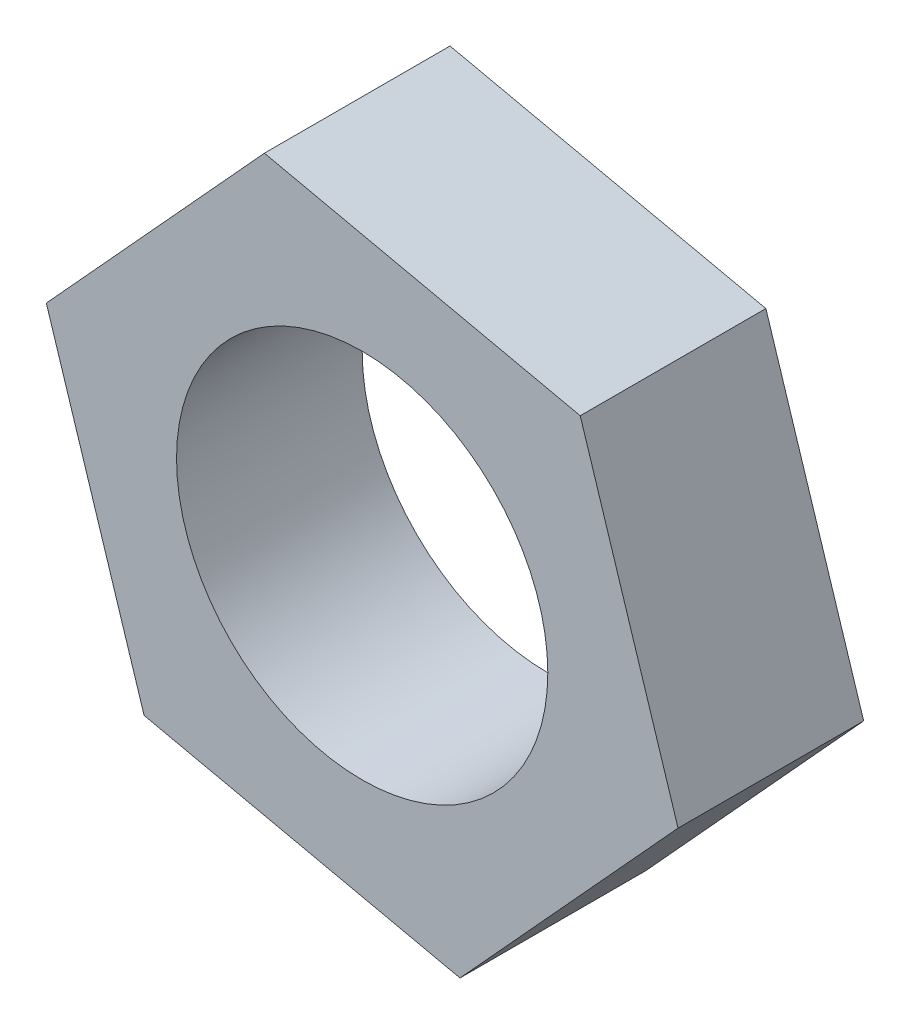
SolidWorks part; units mm, degrees
ref_plane "Front Plane" through (0, 0, 0) normal (0, 0, 1) x (1, 0, 0)
ref_plane "Top Plane" through (0, 0, 0) normal (0, 1, 0) x (1, 0, 0)
ref_plane "Right Plane" through (0, 0, 0) normal (1, 0, 0) x (0, 0, -1)
sketch "Sketch1" plane through (0, 0, 0) normal (0, 0, 1) x (1, 0, 0)
  line L1 (-0.5268, 1.6605) -> (-1.7015, 0.3741)
  line L2 (-1.7015, 0.3741) -> (-1.1747, -1.2865)
  line L3 (-1.1747, -1.2865) -> (0.5268, -1.6605)
  line L4 (0.5268, -1.6605) -> (1.7015, -0.3741)
  line L5 (1.7015, -0.3741) -> (1.1747, 1.2865)
  line L6 (1.1747, 1.2865) -> (-0.5268, 1.6605)
  circle A0 centre (0, 0) radius 1.5087 construction
  circle A1 centre (0, 0) radius 1
  point P10 (-0.5268, 1.6605)
  dimension "D1" = 2
extrude "Boss-Extrude1" add sketch "Sketch1" along normal blind 1
